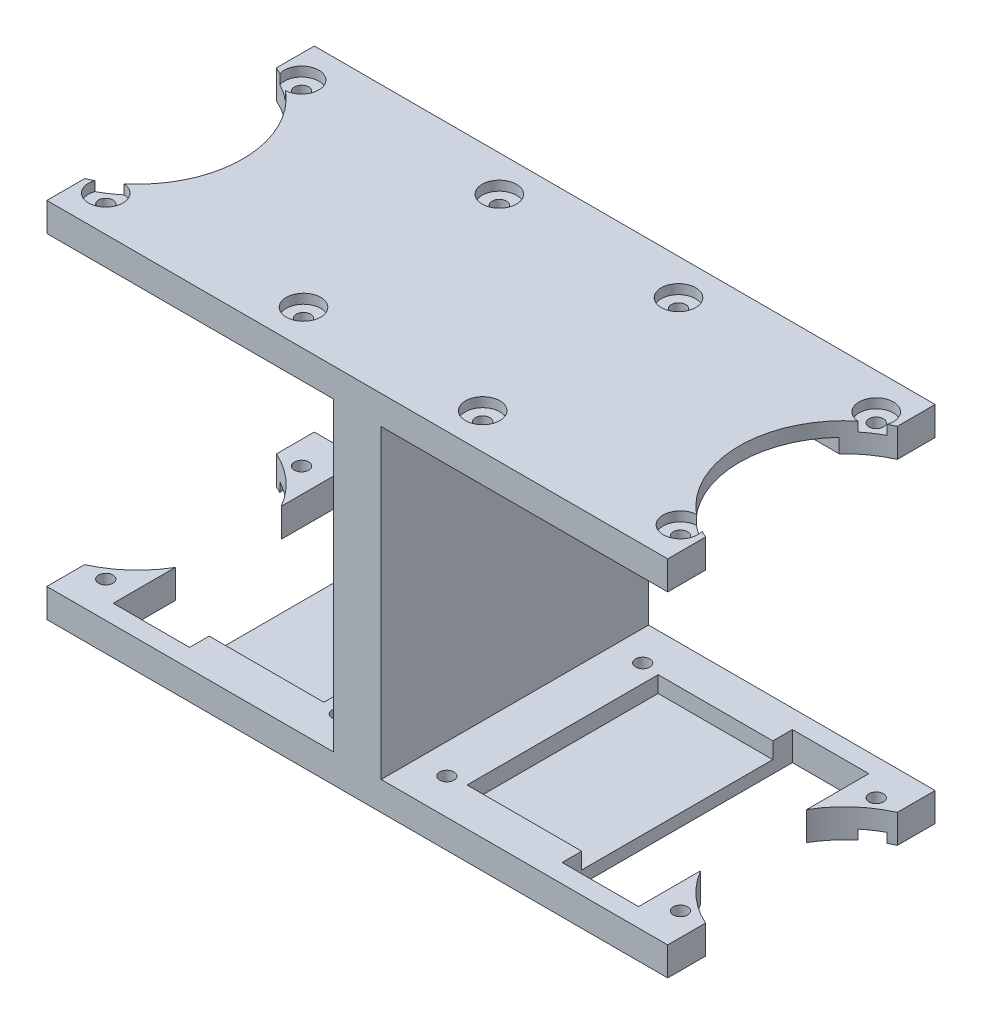
SolidWorks part; units mm, degrees
ref_plane "前视基准面" through (0, 0, 0) normal (0, 0, 1) x (1, 0, 0)
ref_plane "上视基准面" through (0, 0, 0) normal (0, 1, 0) x (1, 0, 0)
ref_plane "右视基准面" through (0, 0, 0) normal (1, 0, 0) x (0, 0, -1)
other "Configuration Table"
sketch "草图1" plane through (0, 0, 0) normal (0, 0, 1) x (1, 0, 0)
  line L1 (0, 0) -> (65, 0)
  line L2 (0, 0) -> (0, 38)
  line L3 (0, 38) -> (65, 38)
  line L4 (65, 0) -> (65, 38)
  dimension "D1" = 65
  dimension "D2" = 38
extrude "凸台-拉伸1" add sketch "草图1" along normal blind 28
sketch "草图2" plane through (0, 0, 28) normal (0, 0, 1) x (1, 0, 0)
  line L0 (32.5, 38) -> (32.5, -49962) construction
  line L1 (65, 38) -> (0, 38) construction
  line L2 (0, 19) -> (50000, 19) construction
  line L3 (0, 38) -> (0, 0) construction
  line L5 (0, 35) -> (30, 35)
  line L6 (0, 35) -> (0, 3)
  line L7 (0, 3) -> (30, 3)
  line L8 (30, 35) -> (30, 3)
  point P4 (32.5, 38)
  point P9 (0, 19)
  point P14 (0, 19)
  dimension "D1" = 32
  dimension "D2" = 30
extrude "切除-拉伸1" cut sketch "草图2" against normal through all
sketch "草图3" plane through (0, 38, 0) normal (0, 1, 0) x (1, 0, 0)
  line L0 (0, -14) -> (50000, -14) construction
  line L1 (0, -28) -> (0, 0) construction
  line L3 (2.42, -3.75) -> (23.12, -3.75) construction
  line L4 (2.42, -3.75) -> (2.42, -24.25) construction
  line L5 (2.42, -24.25) -> (23.12, -24.25) construction
  line L6 (23.12, -3.75) -> (23.12, -24.25) construction
  circle A0 centre (2.42, -3.75) radius 0.75
  circle A1 centre (23.12, -3.75) radius 0.75
  circle A2 centre (23.12, -24.25) radius 0.75
  circle A3 centre (2.42, -24.25) radius 0.75
  point P4 (0, -14)
  point P9 (2.42, -14)
  dimension "D4" = 1.5
  dimension "D5" = 1.5
  dimension "D6" = 1.5
  dimension "D7" = 1.5
  dimension "D1" = 2.42
  dimension "D2" = 20.5
  dimension "D3" = 20.7
extrude "切除-拉伸3" cut sketch "草图3" against normal up to next
sketch "草图4" plane through (0, 0, 0) normal (-1, 0, 0) x (0, 0, 1)
  line L0 (14, 38) -> (14, -49962) construction
  line L1 (28, 38) -> (0, 38) construction
  line L2 (0, 35) -> (28, 35) construction
  line L3 (6.5, 36.5) -> (21.5, 36.5)
  line L4 (6.5, 36.5) -> (6.5, 35)
  line L5 (6.5, 35) -> (21.5, 35)
  line L6 (21.5, 36.5) -> (21.5, 35)
  point P4 (14, 38)
  point P9 (14, 35)
  dimension "D1" = 15
  dimension "D2" = 1.5
extrude "切除-拉伸4" cut sketch "草图4" against normal up to surface (30 mm away) up to face at (30, 19, 14)
sketch "草图5" plane through (0, 38, 0) normal (0, 1, 0) x (1, 0, 0)
  line L0 (0, -14) -> (50000, -14) construction
  line L1 (0, -28) -> (0, 0) construction
  circle A0 centre (-4.5, -14) radius 11
  point P4 (0, -14)
  point P7 (-4.6268, -14)
  dimension "D1" = 22
  dimension "D2" = 4.5
extrude "切除-拉伸5" cut sketch "草图5" against normal through all
sketch "草图6" plane through (0, 0, 0) normal (0, -1, 0) x (1, 0, 0)
  line L1 (2.42, 24.25) -> (26.87, 24.25) construction
  line L2 (2.42, 24.25) -> (2.42, 3.75) construction
  line L3 (2.42, 3.75) -> (26.87, 3.75) construction
  line L4 (26.87, 24.25) -> (26.87, 3.75) construction
  circle A0 centre (2.42, 3.75) radius 0.75 construction
  circle A1 centre (2.42, 24.25) radius 0.75 construction
  circle A2 centre (2.42, 3.75) radius 0.75
  circle A3 centre (2.42, 24.25) radius 0.75
  circle A4 centre (26.87, 24.25) radius 0.75
  circle A5 centre (26.87, 3.75) radius 0.75
  dimension "D2" = 1.5
  dimension "D3" = 1.5
  dimension "D1" = 24.45
extrude "切除-拉伸6" cut sketch "草图6" against normal up to next
sketch "草图7" plane through (0, 0, 0) normal (0, -1, 0) x (1, 0, 0)
  line L0 (65, 14) -> (50065, 14) construction
  line L1 (65, 28) -> (65, 0) construction
  line L3 (5, 26.0513) -> (13, 26.0513)
  line L4 (5, 26.0513) -> (5, 1.9487)
  line L5 (5, 1.9487) -> (13, 1.9487)
  line L6 (13, 26.0513) -> (13, 1.9487)
  line L9 (0, 28) -> (0, 24.0374) construction
  point P4 (65, 14)
  point P9 (5, 14)
  dimension "D1" = 5
  dimension "D2" = 8
extrude "切除-拉伸7" cut sketch "草图7" against normal up to next
sketch "草图8" plane through (0, 38, 0) normal (0, 1, 0) x (1, 0, 0)
  circle A0 centre (23.12, -3.75) radius 1.8
  circle A1 centre (2.42, -3.75) radius 1.8
  circle A2 centre (2.42, -24.25) radius 1.8
  circle A3 centre (23.12, -24.25) radius 1.8
  dimension "D1" = 3.6
  dimension "D2" = 3.6
  dimension "D3" = 3.6
  dimension "D4" = 3.6
extrude "切除-拉伸8" cut sketch "草图8" against normal offset from surface (1 mm away) 2 up to face at (23.12, 35, 4.5)
sketch "草图9" plane through (0, 0, 0) normal (0, -1, 0) x (1, 0, 0)
  circle A0 centre (2.42, 24.25) radius 1.8
  circle A1 centre (26.87, 24.25) radius 1.8
  circle A2 centre (26.87, 3.75) radius 1.8
  circle A3 centre (2.42, 3.75) radius 1.8
  dimension "D1" = 3.6
  dimension "D2" = 3.6
  dimension "D3" = 3.6
  dimension "D4" = 3.6
extrude "切除-拉伸9" cut sketch "草图9" against normal offset from surface (1 mm away) 2 up to face at (26.87, 3, 3)
sketch "草图10" plane through (13, 0, 0) normal (-1, 0, 0) x (0, 0, 1)
  line L0 (14, 3) -> (14, 50003) construction
  line L1 (26.0513, 3) -> (1.9487, 3) construction
  line L3 (4, 3) -> (24, 3)
  line L4 (4, 3) -> (4, 1.3)
  line L5 (4, 1.3) -> (24, 1.3)
  line L6 (24, 3) -> (24, 1.3)
  point P4 (14, 3)
  point P9 (14, 3)
  dimension "D1" = 1.7
  dimension "D2" = 20
extrude "切除-拉伸10" cut sketch "草图10" against normal blind 12
ref_plane "基准面1" through (32.5, 0, 0) normal (-1, 0, 0) x (0, 0, 1)
mirror "镜向1" about plane through (32.5, 0, 0) normal (-1, 0, 0) of "切除-拉伸3", "切除-拉伸4", "切除-拉伸5", "切除-拉伸6", "切除-拉伸7", "切除-拉伸8", "切除-拉伸9", "切除-拉伸10", "切除-拉伸1"
